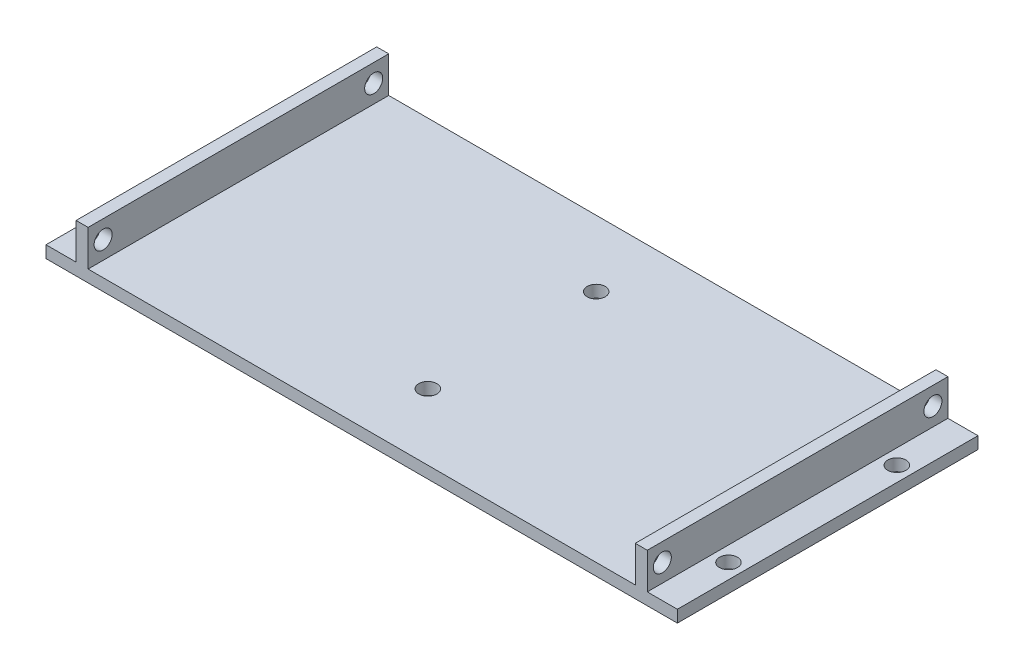
SolidWorks part; units mm, degrees
ref_plane "前视基准面" through (0, 0, 0) normal (0, 0, 1) x (1, 0, 0)
ref_plane "上视基准面" through (0, 0, 0) normal (0, 1, 0) x (1, 0, 0)
ref_plane "右视基准面" through (0, 0, 0) normal (1, 0, 0) x (0, 0, -1)
sketch "草图1" plane through (0, 0, 0) normal (0, 1, 0) x (1, 0, 0)
  line L1 (-52.5, -25) -> (52.5, -25)
  line L2 (-52.5, -25) -> (-52.5, 25)
  line L3 (-52.5, 25) -> (52.5, 25)
  line L4 (52.5, -25) -> (52.5, 25)
  line L5 (-52.5, -25) -> (52.5, 25) construction
  line L6 (-52.5, 25) -> (52.5, -25) construction
  point P0 (0, 0)
  dimension "D1" = 105
  dimension "D2" = 50
extrude "凸台-拉伸1" add sketch "草图1" along normal blind 2
sketch "草图6" plane through (0, 2, 0) normal (0, 1, 0) x (1, 0, 0)
  line L0 (52.5, 25) -> (-52.5, 25) construction
  line L1 (-45.5, -25) -> (-47.5, -25)
  line L2 (-45.5, -25) -> (-45.5, 25)
  line L3 (-45.5, 25) -> (-47.5, 25)
  line L4 (-47.5, -25) -> (-47.5, 25)
  line L5 (-45.5, -25) -> (-47.5, 25) construction
  line L6 (-45.5, 25) -> (-47.5, -25) construction
  line L8 (47.5, -25) -> (45.5, -25)
  line L9 (47.5, -25) -> (47.5, 25)
  line L10 (47.5, 25) -> (45.5, 25)
  line L11 (45.5, -25) -> (45.5, 25)
  line L12 (47.5, -25) -> (45.5, 25) construction
  line L13 (47.5, 25) -> (45.5, -25) construction
  point P0 (-46.5, 0)
  point P7 (46.5, 0)
  dimension "D1" = 46.5
  dimension "D2" = 2
  dimension "D3" = 2
  dimension "D4" = 46.5
extrude "凸台-拉伸3" add sketch "草图6" along normal blind 6
sketch "草图7" plane through (0, 2, 0) normal (0, 1, 0) x (1, 0, 0)
  line L1 (-50, 14) -> (50, 14) construction
  line L2 (-50, 14) -> (-50, -14) construction
  line L3 (-50, -14) -> (50, -14) construction
  line L4 (50, 14) -> (50, -14) construction
  line L5 (-50, 14) -> (50, -14) construction
  line L6 (-50, -14) -> (50, 14) construction
  circle A0 centre (-50, 14) radius 1.5
  circle A1 centre (-50, -14) radius 1.5
  circle A2 centre (50, 14) radius 1.5
  circle A3 centre (50, -14) radius 1.5
  circle A4 centre (0, 14) radius 1.5
  circle A5 centre (0, -14) radius 1.5
  point P0 (0, 0)
  dimension "D1" = 100
  dimension "D2" = 28
extrude "切除-拉伸3" cut sketch "草图7" against normal blind 6
sketch "草图8" plane through (-47.5, 0, 0) normal (-1, 0, 0) x (0, 0, 1)
  line L0 (-25, 2) -> (25, 2) construction
  circle A0 centre (-22.5, 5) radius 1.5
  circle A1 centre (22.5, 5) radius 1.5
  point P0 (-22.5, 5)
  point P1 (22.5, 5)
  dimension "D1" = 3
  dimension "D2" = 22.5
  dimension "D3" = 22.5
  dimension "D4" = 3
extrude "切除-拉伸4" cut sketch "草图8" against normal blind 100
